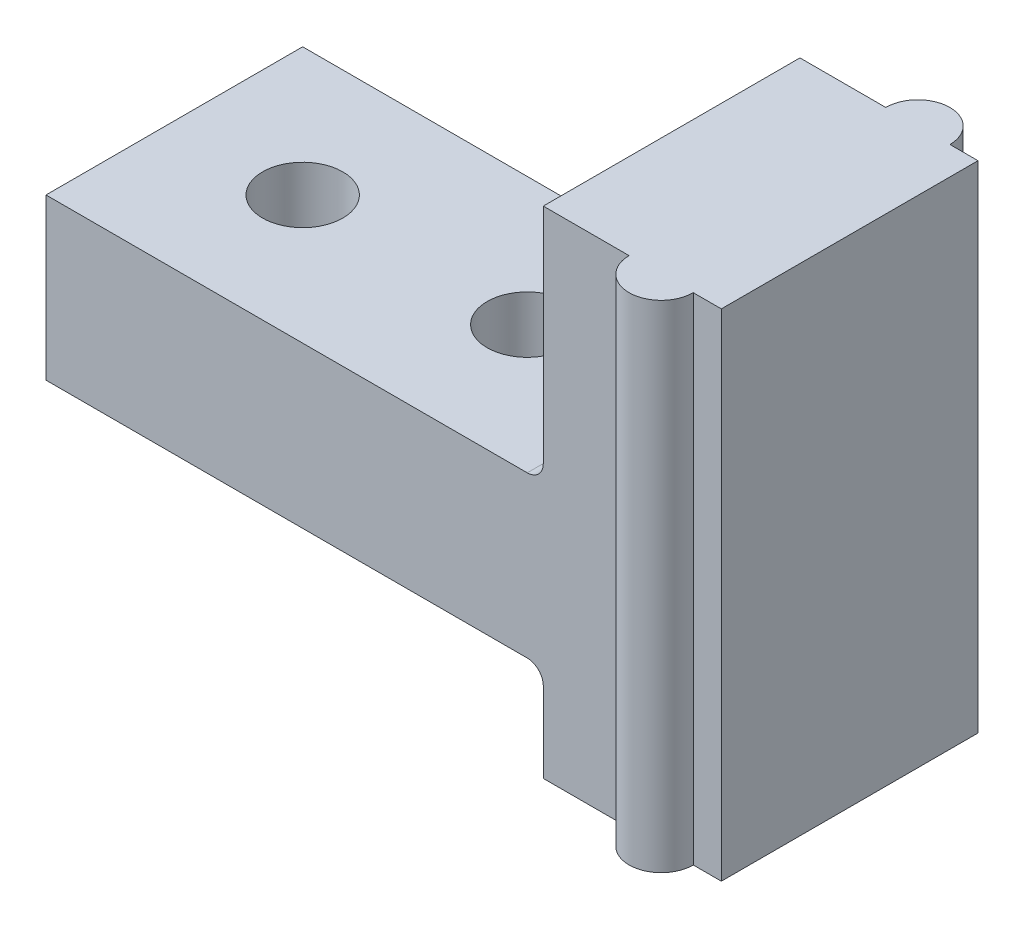
SolidWorks part; units mm, degrees
ref_plane "Front Plane" through (0, 0, 0) normal (0, 0, 1) x (1, 0, 0)
ref_plane "Top Plane" through (0, 0, 0) normal (0, 1, 0) x (1, 0, 0)
ref_plane "Right Plane" through (0, 0, 0) normal (1, 0, 0) x (0, 0, -1)
sketch "Sketch1" plane through (0, 0, 0) normal (0, 0, 1) x (1, 0, 0)
  line L0 (-6.05, 8) -> (-6.05, 15.45) construction
  line L1 (0, 0) -> (-6.05, 0) construction
  line L2 (0, 0) -> (0, 15.45)
  line L3 (0, 15.45) -> (-6.05, 15.45) construction
  line L4 (-6.05, 0) -> (-6.05, 3) construction
  line L5 (-6.05, 3) -> (-21.05, 3)
  line L6 (-5.55, 15.45) -> (-5.55, 0) construction
  line L7 (-6.05, 8) -> (-21.05, 8)
  line L8 (-21.05, 3) -> (-21.05, 8)
  line L9 (-5.55, 0) -> (-5.55, 2.5)
  line L10 (-5.55, 8.5) -> (-5.55, 15.45)
  line L11 (-5.55, 15.45) -> (0, 15.45)
  line L14 (-5.55, 0) -> (0, 0)
  arc A0 (-6.05, 3) -> (-5.55, 2.5) centre (-6.05, 2.5) cw
  arc A1 (-6.05, 8) -> (-5.55, 8.5) centre (-6.05, 8.5) ccw
  dimension "D1" = 5
  dimension "D2" = 21.05
  dimension "D3" = 15
  dimension "D4" = 7.45
  dimension "D5" = 8
  dimension "D6" = 0.5
extrude "Boss-Extrude3" add sketch "Sketch1" along normal mid plane 8
sketch "Sketch2" plane through (0, 0, 0) normal (0, -1, 0) x (1, 0, 0)
  line L0 (-1.875, 4) -> (-1.875, -4) construction
  line L1 (-5.55, 4) -> (0, 4) construction
  line L2 (-5.55, -4) -> (0, -4) construction
  line L3 (0, 4) -> (0, -4) construction
  line L4 (0, 0) -> (-1.875, 0) construction
  line L5 (-0.875, 4) -> (-2.875, 4)
  line L6 (-0.875, -4) -> (-2.875, -4)
  arc A0 (-0.875, 4) -> (-2.875, 4) centre (-1.875, 4) ccw
  arc A1 (-0.875, -4) -> (-2.875, -4) centre (-1.875, -4) cw
  dimension "D2" = 1
  dimension "D1" = 1.875
extrude "Boss-Extrude4" add sketch "Sketch2" against normal up to vertex (15.45 mm away)
sketch "Sketch3" plane through (0, 3, 0) normal (0, -1, 0) x (1, 0, 0)
  line L0 (-21.05, 0) -> (0, 0) construction
  line L1 (-21.05, 4) -> (-21.05, -4) construction
  point P5 (-17.05, 0)
  point P6 (-10.05, 0)
  dimension "D1" = 4
  dimension "D2" = 7
hole_wizard "M3x0.5 Tapped Hole1" positions "Sketch5" profile "Sketch4" tap size "M3x0.5" standard "ANSI Metric" end condition through all
sketch "Sketch5" plane through (0, 3, 0) normal (0, -1, 0) x (-1, 0, 0)
  point P0 (17.05, 0)
  point P3 (10.05, 0)
sketch "Sketch4" plane through (-17.05, 3, 0) normal (1, 0, 0) x (0, 0, -1)
  line L0 (0, 0) -> (0, 12.45)
  line L1 (0, 12.45) -> (1.25, 12.45)
  line L2 (1.25, 12.45) -> (1.25, 0)
  line L5 (1.25, 0) -> (0, 0)
  line L11 (0, -6.35) -> (0, 107.95) construction
  dimension "Thru Tap Drill Dia." = 2.5
  dimension "Thru Tap Drill Depth" = 12.45
cosmetic thread "Hole Thread1" parameters "D2"=3
cosmetic thread "Hole Thread2" parameters "D2"=3
